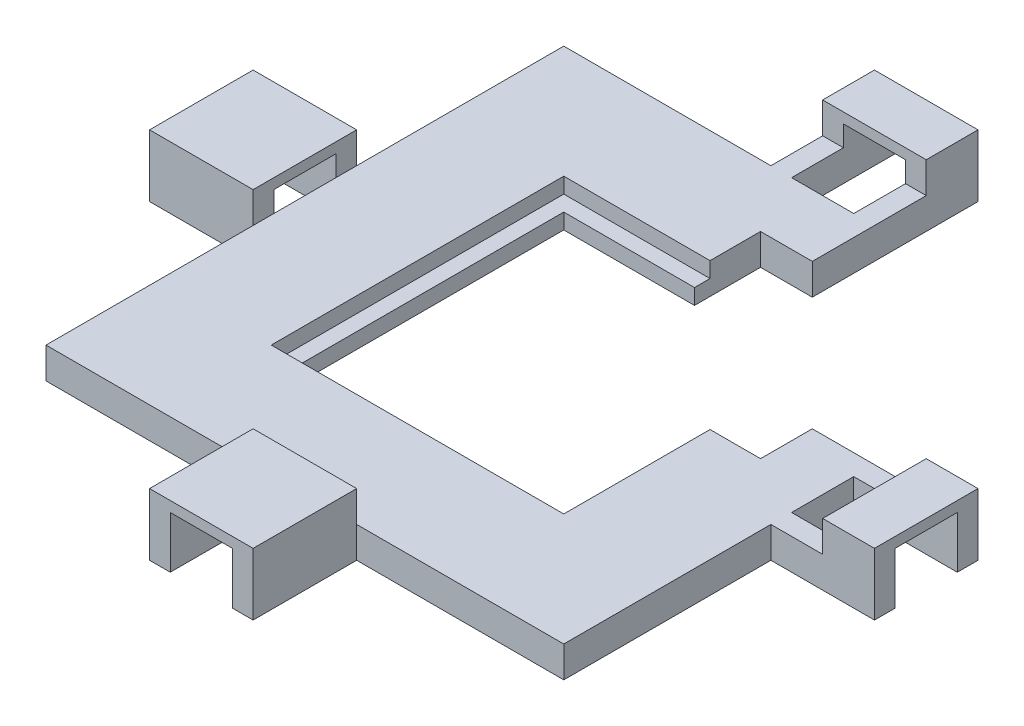
SolidWorks part; units mm, degrees
ref_plane "Front Plane" through (0, 0, 0) normal (0, 0, 1) x (1, 0, 0)
ref_plane "Top Plane" through (0, 0, 0) normal (0, 1, 0) x (1, 0, 0)
ref_plane "Right Plane" through (0, 0, 0) normal (1, 0, 0) x (0, 0, -1)
sketch "Sketch1" plane through (0, 0, 0) normal (0, 1, 0) x (1, 0, 0)
  line L0 (-50, 50) -> (-10, 50)
  line L1 (-10, 50) -> (-10, 70)
  line L2 (-10, -70) -> (10, -70)
  line L3 (-70, -10) -> (-70, 10)
  line L4 (-10, 70) -> (10, 70)
  line L7 (10, 70) -> (10, 25.25)
  line L8 (10, 25.25) -> (-25.25, 25.25)
  line L9 (-25.25, 25.25) -> (-25.25, -25.25)
  line L10 (25.25, 10) -> (70, 10)
  line L11 (70, 10) -> (70, -10)
  line L16 (70, -10) -> (50, -10)
  line L17 (50, -10) -> (50, -50)
  line L18 (50, -50) -> (10, -50)
  line L19 (10, -50) -> (10, -70)
  line L25 (-10, -70) -> (-10, -50)
  line L26 (-10, -50) -> (-50, -50)
  line L27 (-50, -50) -> (-50, -10)
  line L28 (-50, -10) -> (-70, -10)
  line L34 (-70, 10) -> (-50, 10)
  line L35 (-50, 10) -> (-50, 50)
  line L36 (-25.25, -25.25) -> (25.25, -25.25)
  line L37 (25.25, -25.25) -> (25.25, 10)
extrude "Boss-Extrude10" add sketch "Sketch1" along normal blind 12 contours L8 L9 L36 L37 L10 L11 L16 L17 L18 L19 L2 L25 L26 L27 L28 L3 L34 L35 L0 L1 L4 L7
sketch "Sketch6" plane through (0, 12, 0) normal (0, 1, 0) x (1, 0, 0)
  line L0 (50, -10) -> (50, -50) construction
  line L1 (-50, 50) -> (50, 50)
  line L2 (-50, 50) -> (-50, -50)
  line L3 (-50, -50) -> (50, -50)
  line L4 (50, 50) -> (50, -50)
extrude "Cut-Extrude1" cut sketch "Sketch6" against normal blind 6
sketch "Sketch7" plane through (0, 0, 0) normal (0, -1, 0) x (-1, 0, 0)
  line L0 (70, -10) -> (70, 10) construction
  line L1 (70, -6) -> (50, -6)
  line L2 (70, -6) -> (70, 6)
  line L3 (70, 6) -> (50, 6)
  line L4 (50, -6) -> (50, 6)
  line L5 (10, -70) -> (-10, -70) construction
  line L6 (6, -70) -> (-6, -70)
  line L7 (6, -70) -> (6, -50)
  line L8 (6, -50) -> (-6, -50)
  line L9 (-6, -70) -> (-6, -50)
  line L10 (-70, 10) -> (-70, -10) construction
  line L11 (-70, -6) -> (-50, -6)
  line L12 (-70, -6) -> (-70, 6)
  line L13 (-70, 6) -> (-50, 6)
  line L14 (-50, -6) -> (-50, 6)
  line L15 (10, 70) -> (-10, 70) construction
  line L16 (-6, 70) -> (6, 70)
  line L17 (-6, 70) -> (-6, 50)
  line L18 (-6, 50) -> (6, 50)
  line L19 (6, 70) -> (6, 50)
  point P24 (0, 0)
  point P25 (0, 0)
  point P26 (0, 0)
  point P27 (0, 0)
  point P28 (0, 0)
  point P29 (0, 0)
  point P30 (0, 0)
  point P31 (0, 0)
  point P32 (0, 0)
  point P33 (0, 0)
  point P34 (0, 0)
  point P35 (0, 0)
  point P36 (0, 0)
  point P37 (0, 0)
extrude "Cut-Extrude2" cut sketch "Sketch7" against normal blind 10
sketch "Sketch8" plane through (0, 6, 0) normal (0, 1, 0) x (1, 0, 0)
  line L1 (-28.25, 28.25) -> (28.25, 28.25)
  line L2 (-28.25, 28.25) -> (-28.25, -28.25)
  line L3 (-28.25, -28.25) -> (28.25, -28.25)
  line L4 (28.25, 28.25) -> (28.25, -28.25)
  point P4 (0, 0)
  point P5 (0, 0)
extrude "Cut-Extrude3" cut sketch "Sketch8" against normal blind 3
sketch "Sketch10" plane through (0, 12, 0) normal (0, 1, 0) x (1, 0, 0)
  line L0 (-10, 50) -> (-10, 70) construction
  line L1 (-10, 60) -> (10, 60)
  line L2 (-10, 60) -> (-10, 50)
  line L3 (-10, 50) -> (10, 50)
  line L4 (10, 60) -> (10, 50)
  line L5 (50, 10) -> (70, 10) construction
  line L6 (60, 10) -> (50, 10)
  line L7 (60, 10) -> (60, -10)
  line L8 (60, -10) -> (50, -10)
  line L9 (50, 10) -> (50, -10)
extrude "Cut-Extrude6" cut sketch "Sketch10" against normal blind 6
sketch "Sketch11" plane through (0, 6, 0) normal (0, 1, 0) x (1, 0, 0)
  line L0 (10, 60) -> (10, 28.25) construction
  line L1 (10, 38) -> (0, 38)
  line L2 (10, 38) -> (10, 25.25)
  line L3 (10, 25.25) -> (0, 25.25)
  line L4 (0, 38) -> (0, 25.25)
  line L5 (10, 25.25) -> (-25.25, 25.25) construction
  line L6 (28.25, 10) -> (60, 10) construction
  line L7 (38, 10) -> (25.25, 10)
  line L8 (38, 10) -> (38, 0)
  line L9 (38, 0) -> (25.25, 0)
  line L10 (25.25, 10) -> (25.25, 0)
  line L11 (25.25, -25.25) -> (25.25, 10) construction
  point P16 (0, 0)
  point P17 (0, 0)
  point P18 (0, 0)
extrude "Cut-Extrude7" cut sketch "Sketch11" against normal through all
